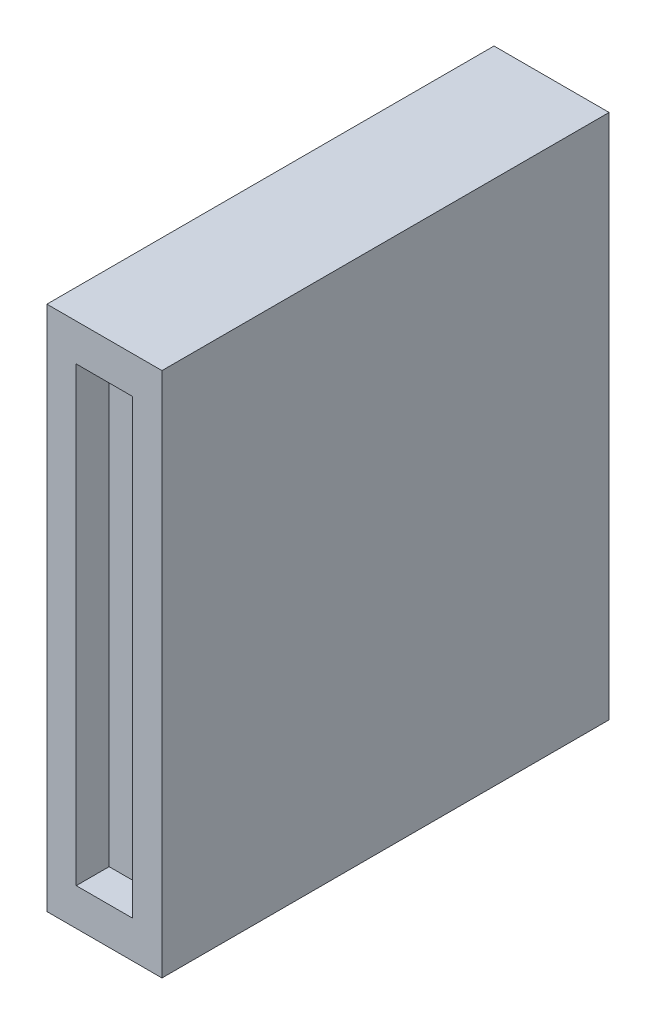
SolidWorks part; units mm, degrees
ref_plane "Front Plane" through (0, 0, 0) normal (0, 0, 1) x (1, 0, 0)
ref_plane "Top Plane" through (0, 0, 0) normal (0, 1, 0) x (1, 0, 0)
ref_plane "Right Plane" through (0, 0, 0) normal (1, 0, 0) x (0, 0, -1)
sketch "Sketch1" plane through (0, 0, 0) normal (0, 0, 1) x (1, 0, 0)
  line L1 (-8.75, -40) -> (8.75, -40)
  line L2 (-8.75, -40) -> (-8.75, 40)
  line L3 (-8.75, 40) -> (8.75, 40)
  line L4 (8.75, -40) -> (8.75, 40)
  line L5 (-8.75, -40) -> (8.75, 40) construction
  line L6 (-8.75, 40) -> (8.75, -40) construction
  point P0 (0, 0)
  dimension "D1" = 80
  dimension "D2" = 17.5
extrude "Boss-Extrude1" add sketch "Sketch1" along normal blind 68
sketch "Sketch2" plane through (0, 0, 68) normal (0, 0, 1) x (1, 0, 0)
  line L1 (-4.2881, -34.3572) -> (4.2881, -34.3572)
  line L2 (-4.2881, -34.3572) -> (-4.2881, 34.3572)
  line L3 (-4.2881, 34.3572) -> (4.2881, 34.3572)
  line L4 (4.2881, -34.3572) -> (4.2881, 34.3572)
  line L5 (-4.2881, -34.3572) -> (4.2881, 34.3572) construction
  line L6 (-4.2881, 34.3572) -> (4.2881, -34.3572) construction
  point P0 (0, 0)
extrude "Cut-Extrude1" cut sketch "Sketch2" against normal blind 5
